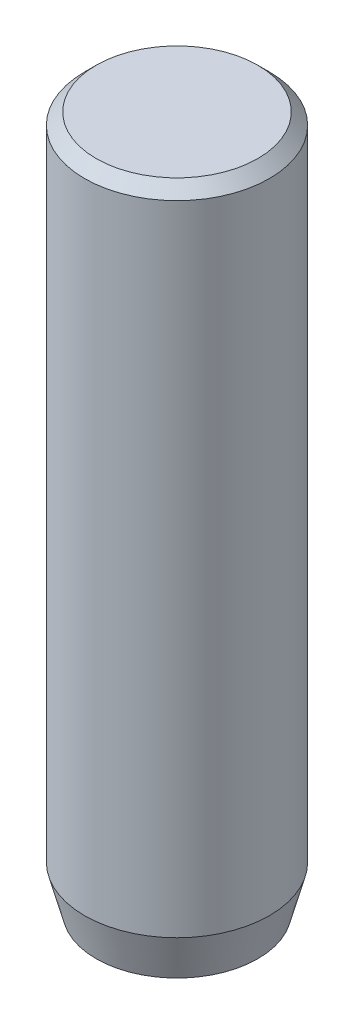
SolidWorks part; units mm, degrees
ref_plane "前基準面" through (0, 0, 0) normal (0, 0, 1) x (1, 0, 0)
ref_plane "上基準面" through (0, 0, 0) normal (0, 1, 0) x (1, 0, 0)
ref_plane "右基準面" through (0, 0, 0) normal (1, 0, 0) x (0, 0, -1)
sketch "草圖1" plane through (0, 0, 0) normal (0, 1, 0) x (1, 0, 0)
  circle A0 centre (0, 0) radius 4
  dimension "D1" = 8
extrude "伸長1" add sketch "草圖1" along normal mid plane 30
chamfer "導角1" distance 0.5 angle 45 1 edges at (0, 15, 4)
chamfer "導角2" distance 0.5 angle 75 1 edges at (0, -15, 4)
